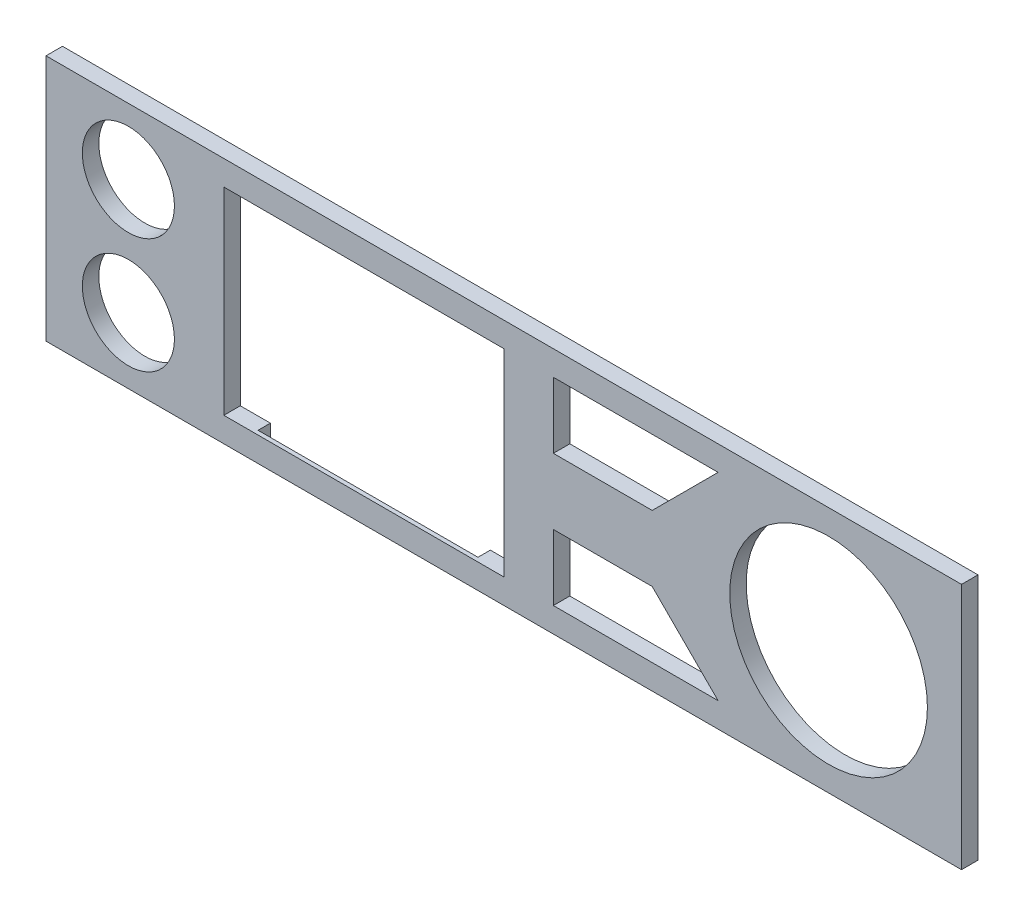
SolidWorks part; units mm, degrees
ref_plane "Front Plane" through (0, 0, 0) normal (0, 0, 1) x (1, 0, 0)
ref_plane "Top Plane" through (0, 0, 0) normal (0, 1, 0) x (1, 0, 0)
ref_plane "Right Plane" through (0, 0, 0) normal (1, 0, 0) x (0, 0, -1)
sketch "Sketch2" plane through (0, 0, 0) normal (0, 0, 1) x (1, 0, 0)
  line L0 (-36.596, 27) -> (-29.55, 27)
  line L1 (0, 0) -> (-111.14, 0)
  line L2 (0, 0) -> (0, 30)
  line L3 (0, 30) -> (-111.14, 30)
  line L4 (-111.14, 0) -> (-111.14, 30)
  line L9 (-49.55, 27) -> (-36.596, 27)
  line L10 (-49.55, 27) -> (-49.55, 19)
  line L11 (-49.55, 19) -> (-37.55, 19)
  line L13 (-49.55, 3) -> (-37.006, 3)
  line L14 (-49.55, 3) -> (-49.55, 11)
  line L15 (-49.55, 11) -> (-37.55, 11)
  line L17 (-89.55, 27) -> (-55.55, 27)
  line L18 (-89.55, 27) -> (-89.55, 3)
  line L19 (-89.55, 3) -> (-55.55, 3)
  line L20 (-55.55, 27) -> (-55.55, 3)
  line L21 (-29.55, 27) -> (-37.55, 19)
  line L22 (-37.55, 11) -> (-29.55, 3)
  line L23 (-29.55, 3) -> (-37.006, 3)
  circle A2 centre (-101.14, 22) radius 5.59
  circle A3 centre (-101.14, 8) radius 5.59
  circle A4 centre (-16.14, 15) radius 12
  dimension "D6" = 34
  dimension "D17" = 15
  dimension "D28" = 24
  dimension "D30" = 11.18
  dimension "D31" = 11.18
  dimension "D1" = 111.14
  dimension "D2" = 30
  dimension "D4" = 8
  dimension "D5" = 10
  dimension "D7" = 10
  dimension "D8" = 8
  dimension "D12" = 21.59
  dimension "D13" = 3
  dimension "D14" = 3
  dimension "D18" = 8
  dimension "D19" = 8
  dimension "D20" = 3
  dimension "D21" = 3
  dimension "D22" = 6
  dimension "D23" = 6
  dimension "D24" = 8
  dimension "D25" = 12
  dimension "D26" = 12
  dimension "D27" = 8
  dimension "D29" = 16.14
extrude "Boss-Extrude1" add sketch "Sketch2" along normal blind 2
sketch "Sketch3" plane through (0, 0, 0) normal (0, 0, -1) x (-1, 0, 0)
  line L0 (89.55, 3) -> (55.55, 3) construction
  line L1 (59.2, 3) -> (85.9, 3)
  line L2 (59.2, 3) -> (59.2, 0.75)
  line L3 (59.2, 0.75) -> (85.9, 0.75)
  line L4 (85.9, 3) -> (85.9, 0.75)
  line L5 (55.55, 3) -> (55.55, 27) construction
  dimension "D1" = 2.25
  dimension "D2" = 26.7
  dimension "D3" = 3.65
extrude "Cut-Extrude1" cut sketch "Sketch3" against normal blind 1.5
